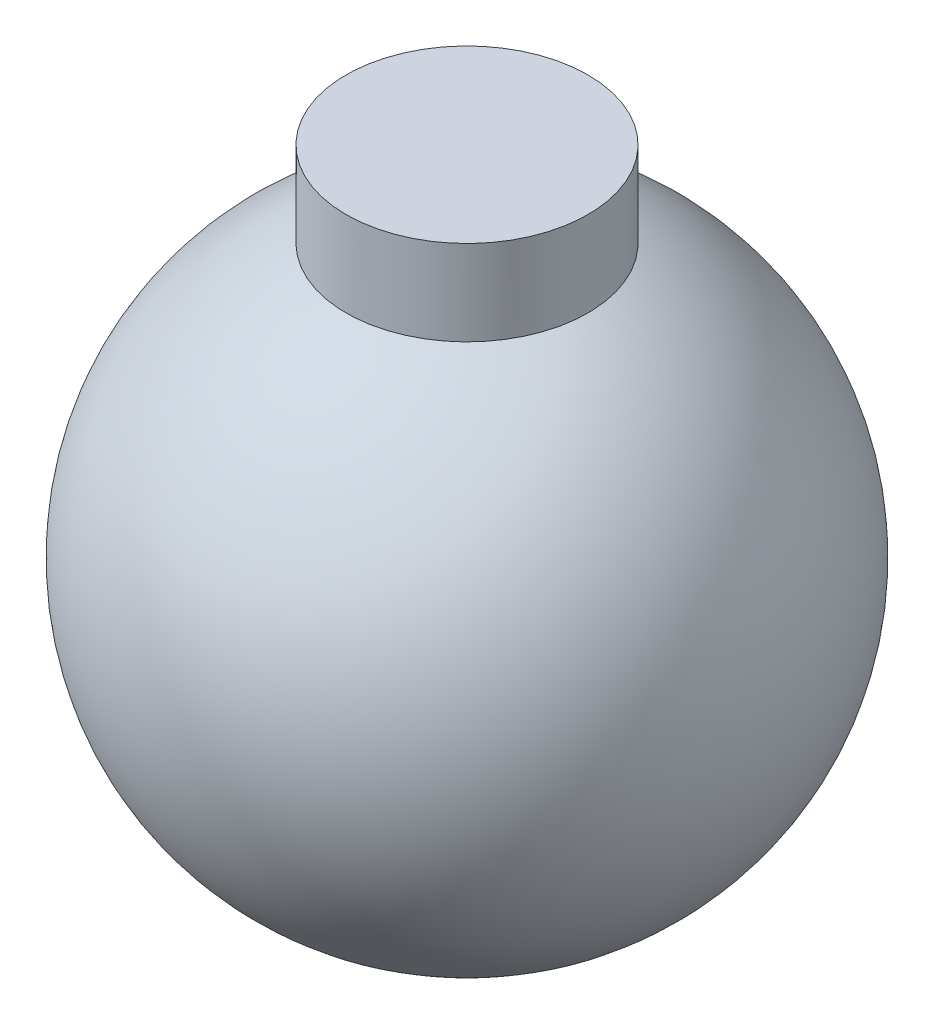
SolidWorks part; units mm, degrees
ref_plane "前视基准面" through (0, 0, 0) normal (0, 0, 1) x (1, 0, 0)
ref_plane "上视基准面" through (0, 0, 0) normal (0, 1, 0) x (1, 0, 0)
ref_plane "右视基准面" through (0, 0, 0) normal (1, 0, 0) x (0, 0, -1)
other "Configuration Table"
sketch "草图1" plane through (0, 0, 0) normal (0, 1, 0) x (1, 0, 0)
  line L0 (0, -25) -> (0, 25) construction
  line L1 (0, 25) -> (0, -25)
  arc A0 (0, -25) -> (0, 25) centre (0, 0) ccw
  point P6 (0, 0)
  dimension "D1" = 50
revolve "旋转1" add sketch "草图1" angle 360 about L0
sketch "草图2" plane through (0, 0, 0) normal (0, 1, 0) x (1, 0, 0)
  circle A0 centre (0, 0) radius 10.1606
extrude "凸台-拉伸1" add sketch "草图2" along normal blind 30
